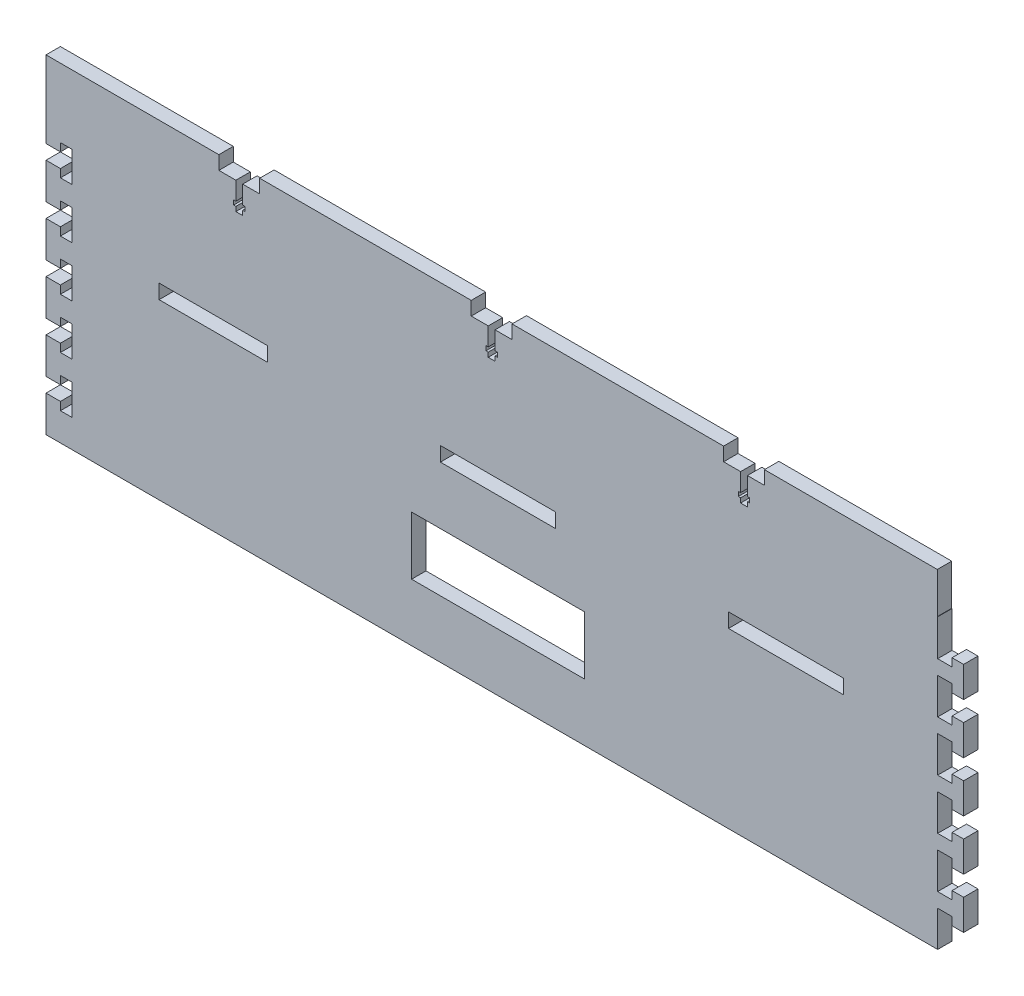
SolidWorks part; units mm, degrees
ref_plane "Front Plane" through (0, 0, 0) normal (0, 0, 1) x (1, 0, 0)
ref_plane "Top Plane" through (0, 0, 0) normal (0, 1, 0) x (1, 0, 0)
ref_plane "Right Plane" through (0, 0, 0) normal (1, 0, 0) x (0, 0, -1)
sketch "Sketch1" plane through (0, 0, 0) normal (0, 0, 1) x (1, 0, 0)
  line L1 (-196.5325, 63.5) -> (196.5325, 63.5)
  line L2 (-196.5325, 63.5) -> (-196.5325, -63.5)
  line L3 (-196.5325, -63.5) -> (196.5325, -63.5)
  line L4 (196.5325, 63.5) -> (196.5325, -63.5)
  line L5 (-196.5325, 63.5) -> (196.5325, -63.5) construction
  line L6 (-196.5325, -63.5) -> (196.5325, 63.5) construction
  point P0 (0, 0)
extrude "Boss-Extrude1" add sketch "Sketch1" along normal blind 6.35
sketch "Sketch2" plane through (0, 0, 6.35) normal (0, 0, 1) x (1, 0, 0)
  line L0 (-196.5325, -63.5) -> (196.5325, -63.5) construction
  line L1 (-35.3695, -12.446) -> (40.8305, -12.446)
  line L2 (-35.3695, -12.446) -> (-35.3695, -38.1)
  line L3 (-35.3695, -38.1) -> (40.8305, -38.1)
  line L4 (40.8305, -12.446) -> (40.8305, -38.1)
  line L5 (-35.3695, -12.446) -> (40.8305, -38.1) construction
  line L6 (-35.3695, -38.1) -> (40.8305, -12.446) construction
  line L7 (196.5325, -63.5) -> (196.5325, 63.5) construction
  point P0 (2.7305, -25.273)
  dimension "D1" = 25.4
  dimension "D2" = 193.802
extrude "Cut-Extrude1" cut sketch "Sketch2" against normal blind 6.35
sketch "Sketch3" plane through (0, 0, 6.35) normal (0, 0, 1) x (1, 0, 0)
  line L0 (-196.5325, 47.625) -> (-190.1825, 47.625)
  line L1 (-196.5325, 63.5) -> (-196.5325, -63.5) construction
  line L2 (-190.1825, 47.625) -> (-190.1825, 51.181)
  line L3 (-190.1825, 51.181) -> (-185.1025, 51.181)
  line L4 (-185.1025, 51.181) -> (-185.1025, 37.719)
  line L5 (-185.1025, 37.719) -> (-190.1825, 37.719)
  line L6 (-190.1825, 37.719) -> (-190.1825, 41.275)
  line L7 (-190.1825, 41.275) -> (-196.5325, 41.275)
  line L8 (-196.5325, 41.275) -> (-196.5325, 47.625)
  line L9 (196.5325, 63.5) -> (-196.5325, 63.5) construction
  dimension "D1" = 15.875
  dimension "D2" = 6.35
  dimension "D3" = 3.556
  dimension "D4" = 3.556
  dimension "D5" = 6.35
  dimension "D6" = 5.08
extrude "Cut-Extrude2" cut sketch "Sketch3" against normal blind 6.35
pattern_linear "LPattern1" count 5 spacing 22.225 along (0, -1, 0) of "Cut-Extrude2"
sketch "Sketch4" plane through (0, 0, 6.35) normal (0, 0, 1) x (1, 0, 0)
  line L0 (196.5325, 47.498) -> (202.8825, 47.498)
  line L1 (196.5325, -63.5) -> (196.5325, 63.5) construction
  line L2 (202.8825, 51.054) -> (202.8825, 47.498)
  line L3 (202.8825, 51.054) -> (207.9625, 51.054)
  line L4 (207.9625, 37.592) -> (202.8825, 37.592)
  line L5 (202.8825, 37.592) -> (202.8825, 41.148)
  line L6 (202.8825, 41.148) -> (196.5325, 41.148)
  line L7 (196.5325, 41.148) -> (196.5325, 47.498)
  line L8 (207.9625, 37.592) -> (207.9625, 51.054)
  line L9 (196.5325, 63.5) -> (-196.5325, 63.5) construction
  dimension "D1" = 13.462
  dimension "D2" = 3.556
  dimension "D3" = 3.556
  dimension "D4" = 6.35
  dimension "D5" = 5.08
  dimension "D6" = 6.35
  dimension "D7" = 16.002
extrude "Boss-Extrude2" add sketch "Sketch4" against normal blind 6.35 separate body
pattern_linear "LPattern2" count 5 spacing 22.225 along (0, -1, 0) of "Boss-Extrude2"
sketch3d "3DSketch1"
  line L0 (196.5325, -63.5, 6.35) -> (196.5325, 63.5, 6.35) construction
  point P0 (196.5325, 22.4401, 6.35)
combine bodies "Combine1" operation type add bodies to combine 105 104 106 107 108 109
sketch "Sketch12" plane through (0, 0, 6.35) normal (0, 0, 1) x (1, 0, 0)
  line L0 (-196.5325, 63.5) -> (-196.5325, 81.5)
  line L1 (196.5325, 63.5) -> (-196.5325, 63.5) construction
  line L2 (-196.5325, 63.5) -> (-196.5325, 47.625) construction
  line L3 (-196.5325, 81.5) -> (-120.3325, 81.5)
  line L4 (-120.3325, 81.5) -> (-120.3325, 75.5)
  line L5 (-120.3325, 75.5) -> (-112.8325, 75.5)
  line L6 (-112.8325, 75.5) -> (-112.8325, 67.5)
  line L7 (-112.8325, 67.5) -> (-113.8325, 67.5)
  line L8 (-113.8325, 67.5) -> (-113.8325, 65.5)
  line L9 (-113.8325, 65.5) -> (-112.8325, 65.5)
  line L10 (-112.8325, 65.5) -> (-112.8325, 63.5)
  line L11 (-112.8325, 63.5) -> (-109.8325, 63.5)
  line L12 (-109.8325, 63.5) -> (-109.8325, 65.5)
  line L13 (-109.8325, 65.5) -> (-108.8325, 65.5)
  line L14 (-108.8325, 65.5) -> (-108.8325, 67.5)
  line L15 (-108.8325, 67.5) -> (-109.8325, 67.5)
  line L16 (-109.8325, 67.5) -> (-109.8325, 75.5)
  line L17 (-109.8325, 75.5) -> (-102.3325, 75.5)
  line L18 (-102.3325, 75.5) -> (-102.3325, 81.5)
  line L19 (-102.3325, 81.5) -> (-26.1325, 81.5)
  line L20 (-26.1325, 81.5) -> (-26.1325, 63.5)
  line L21 (-26.1325, 63.5) -> (-196.5325, 63.5)
  dimension "D1" = 18
  dimension "D2" = 6
  dimension "D3" = 8
  dimension "D4" = 2
  dimension "D5" = 2
  dimension "D6" = 7.5
  dimension "D7" = 7.5
  dimension "D8" = 1
  dimension "D9" = 1
  dimension "D10" = 3
  dimension "D11" = 1
  dimension "D12" = 1
  dimension "D13" = 76.2
  dimension "D14" = 76.2
extrude "Boss-Extrude3" add sketch "Sketch12" against normal blind 6.35 separate body contours L21 L10 L9 L8 L7 L6 L5 L4 L3 L0 | L21 L20 L19 L18 L17 L16 L15 L14 L13 L12
pattern_linear "LPattern4" count 3 spacing 111.252 along (1, 0, 0) of "Boss-Extrude3"
combine bodies "Combine2" operation type add bodies to combine 119 120 130 129 131 132 118
sketch "Sketch14" plane through (0, 0, 6.35) normal (0, 0, 1) x (1, 0, 0)
  line L0 (40.8305, -12.446) -> (-35.3695, -12.446) construction
  line L1 (-22.6695, 19.304) -> (28.1305, 19.304)
  line L2 (-22.6695, 19.304) -> (-22.6695, 12.954)
  line L3 (-22.6695, 12.954) -> (28.1305, 12.954)
  line L4 (28.1305, 19.304) -> (28.1305, 12.954)
  line L5 (-22.6695, 19.304) -> (28.1305, 12.954) construction
  line L6 (-22.6695, 12.954) -> (28.1305, 19.304) construction
  line L8 (40.8305, -38.1) -> (40.8305, -12.446) construction
  point P0 (2.7305, 16.129)
  dimension "D1" = 25.4
  dimension "D2" = 50.8
  dimension "D3" = 6.35
  dimension "D4" = 38.1
extrude "Cut-Extrude3" cut sketch "Sketch14" against normal blind 6.35
sketch "Sketch16" plane through (0, 0, 6.35) normal (0, 0, 1) x (1, 0, 0)
  line L0 (28.1305, 19.304) -> (-22.6695, 19.304) construction
  line L1 (104.3305, 19.304) -> (155.1305, 19.304)
  line L2 (104.3305, 19.304) -> (104.3305, 12.954)
  line L3 (104.3305, 12.954) -> (155.1305, 12.954)
  line L4 (155.1305, 19.304) -> (155.1305, 12.954)
  line L5 (104.3305, 19.304) -> (155.1305, 12.954) construction
  line L6 (104.3305, 12.954) -> (155.1305, 19.304) construction
  line L7 (-22.6695, 12.954) -> (28.1305, 12.954) construction
  line L8 (28.1305, 12.954) -> (28.1305, 19.304) construction
  point P0 (129.7305, 16.129)
  dimension "D1" = 76.2
  dimension "D2" = 50.8
extrude "Cut-Extrude4" cut sketch "Sketch16" against normal blind 6.35
sketch "Sketch19" plane through (0, 0, 6.35) normal (0, 0, 1) x (1, 0, 0)
  line L0 (28.1305, 19.304) -> (-22.6695, 19.304) construction
  line L1 (-146.685, 19.304) -> (-98.8695, 19.304)
  line L2 (-146.685, 19.304) -> (-146.685, 12.954)
  line L3 (-146.685, 12.954) -> (-98.8695, 12.954)
  line L4 (-98.8695, 19.304) -> (-98.8695, 12.954)
  line L5 (-146.685, 19.304) -> (-98.8695, 12.954) construction
  line L6 (-146.685, 12.954) -> (-98.8695, 19.304) construction
  line L7 (-22.6695, 19.304) -> (-22.6695, 12.954) construction
  point P0 (-122.7773, 16.129)
  dimension "D1" = 76.2
extrude "Cut-Extrude5" cut sketch "Sketch19" against normal blind 6.35
